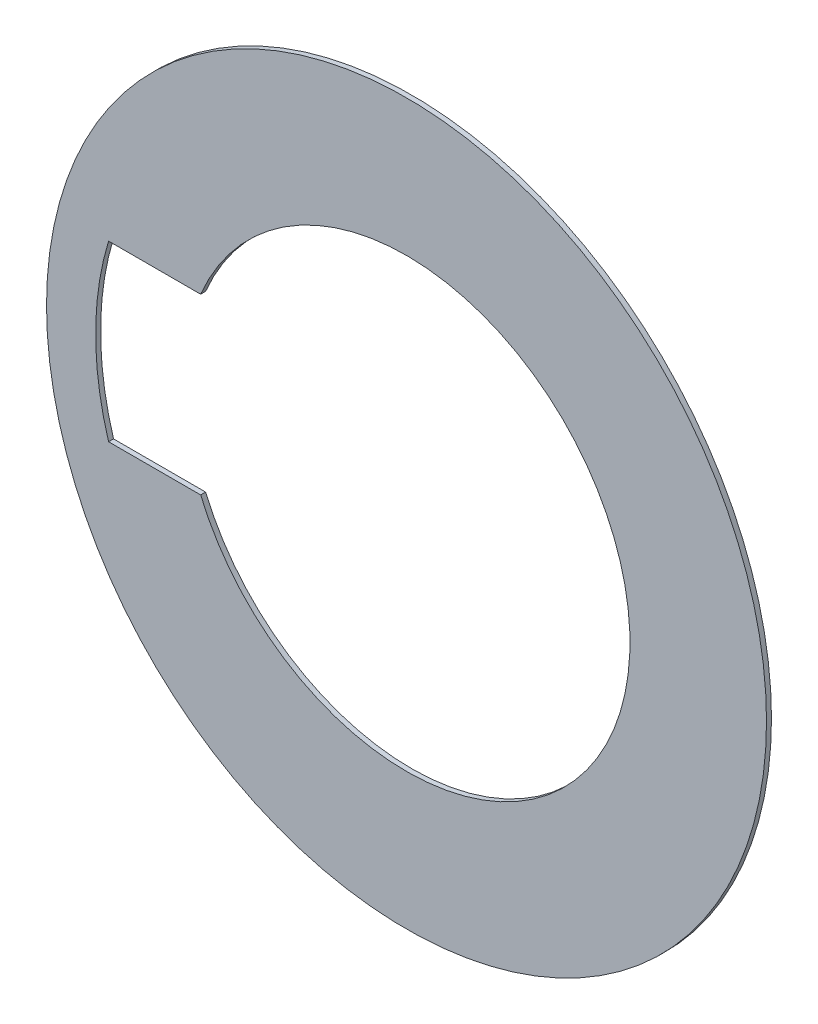
SolidWorks part; units mm, degrees
ref_plane "Front" through (0, 0, 0) normal (0, 0, 1) x (1, 0, 0)
ref_plane "Top" through (0, 0, 0) normal (0, 1, 0) x (1, 0, 0)
ref_plane "Right" through (0, 0, 0) normal (1, 0, 0) x (0, 0, -1)
sketch "Sketch1" plane through (0, 0, 0) normal (0, 0, 1) x (1, 0, 0)
  circle A0 centre (0, 0) radius 184.15
  dimension "D1" = 368.3
extrude "Boss-Extrude1" add sketch "Sketch1" along normal blind 2.54 contours A0
sketch "Sketch2" plane through (0, 0, 2.54) normal (0, 0, 1) x (1, 0, 0)
  line L1 (-105.3028, -44.45) -> (-152.4, -44.45)
  line L3 (-105.3028, 44.45) -> (-152.4, 44.45)
  line L4 (-152.4, -44.45) -> (-152.4, 44.45) construction
  arc A0 (-105.3028, -44.45) -> (-105.3028, 44.45) centre (0, 0) ccw
  arc A1 (-152.4, 44.45) -> (-152.4, -44.45) centre (-6.6263, 0) ccw
  point P14 (-152.4, 0)
  dimension "D1" = 228.6
  dimension "D4" = 152.4
  dimension "D2" = 152.4
  dimension "D3" = 88.9
extrude "Cut-Extrude1" cut sketch "Sketch2" against normal through all both and the other way through all
